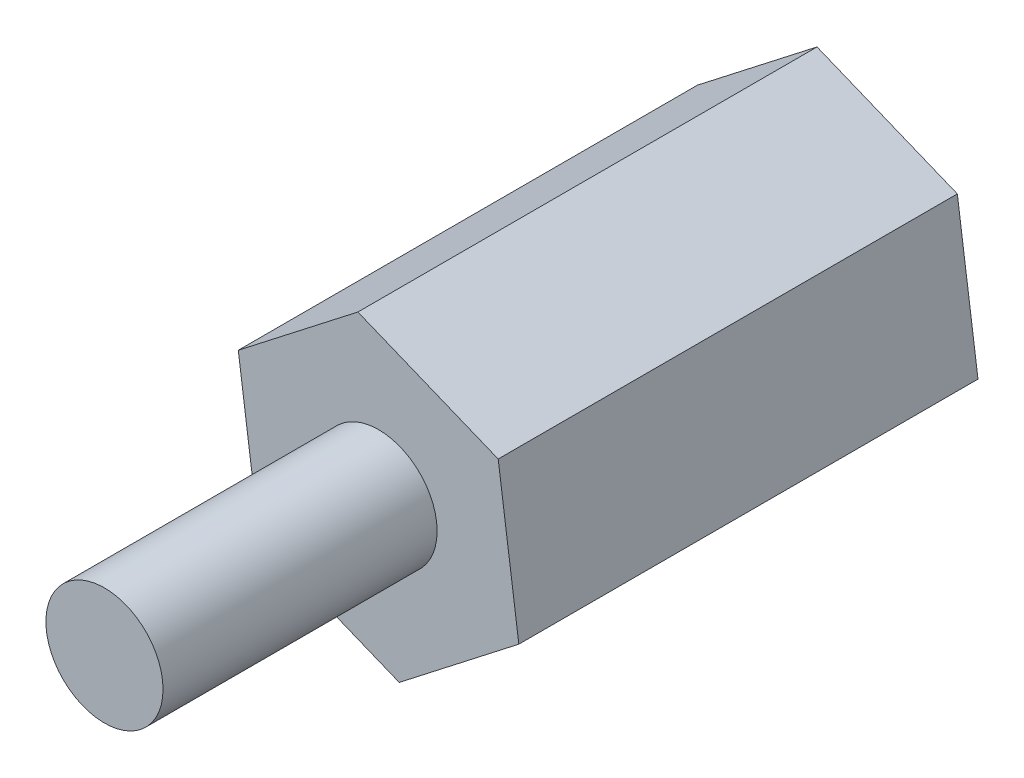
SolidWorks part; units mm, degrees
ref_plane "Front Plane" through (0, 0, 0) normal (0, 0, 1) x (1, 0, 0)
ref_plane "Top Plane" through (0, 0, 0) normal (0, 1, 0) x (1, 0, 0)
ref_plane "Right Plane" through (0, 0, 0) normal (1, 0, 0) x (0, 0, -1)
sketch "Sketch1" plane through (0, 0, 0) normal (0, 0, 1) x (1, 0, 0)
  line L1 (-2.5942, -2.0151) -> (0.4481, -3.2542)
  line L2 (0.4481, -3.2542) -> (3.0422, -1.2391)
  line L3 (3.0422, -1.2391) -> (2.5942, 2.0151)
  line L4 (2.5942, 2.0151) -> (-0.4481, 3.2542)
  line L5 (-0.4481, 3.2542) -> (-3.0422, 1.2391)
  line L6 (-3.0422, 1.2391) -> (-2.5942, -2.0151)
  circle A0 centre (0, 0) radius 2.8448 construction
extrude "Boss-Extrude1" add sketch "Sketch1" along normal blind 9.9568
sketch "Sketch3" plane through (0, 0, 0) normal (0, 0, -1) x (-1, 0, 0)
  circle A0 centre (0, 0) radius 1.27
extrude "Cut-Extrude1" cut sketch "Sketch3" against normal blind 7.4168
sketch "Sketch4" plane through (0, 0, 9.9568) normal (0, 0, 1) x (1, 0, 0)
  circle A0 centre (0, 0) radius 1.27
extrude "Boss-Extrude2" add sketch "Sketch4" along normal blind 5.9436
